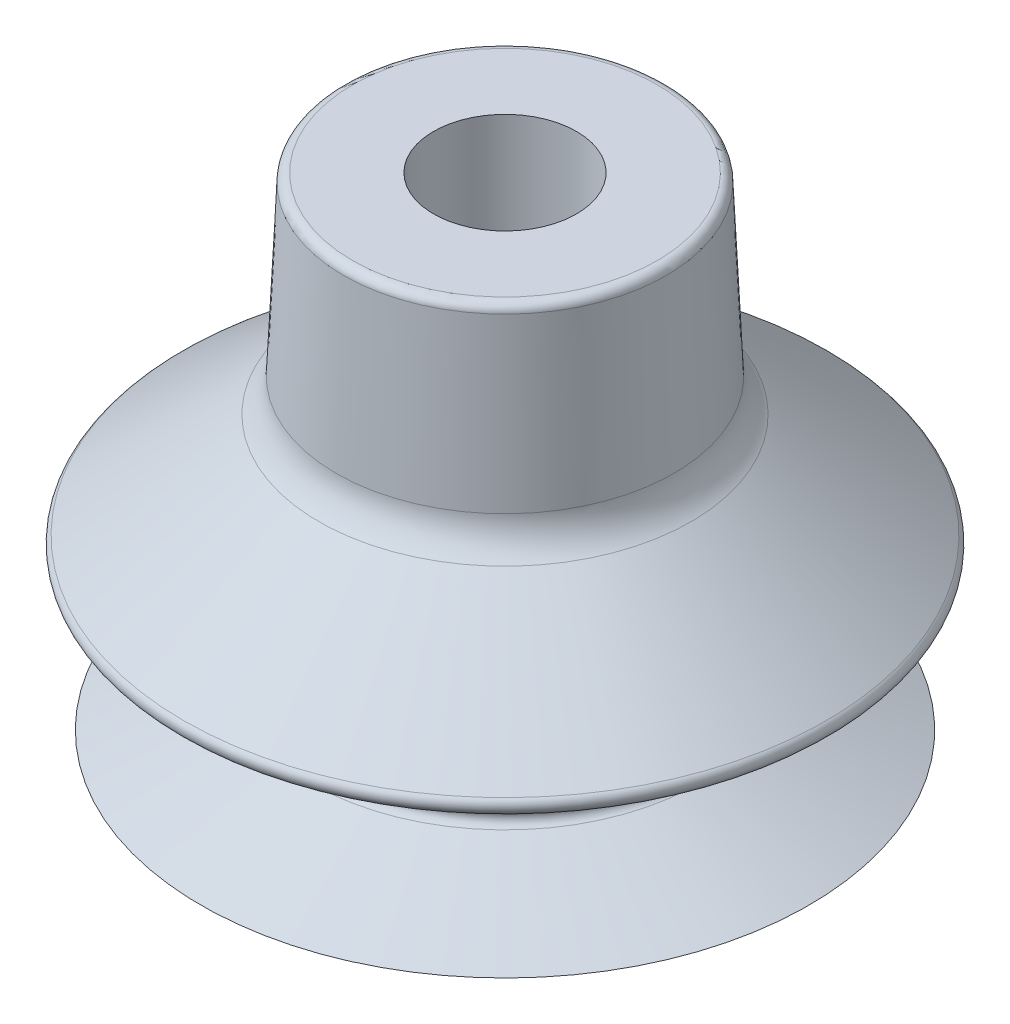
SolidWorks part; units mm, degrees
material "Nylon 6/10"
ref_plane "Plan de face" through (0, 0, 0) normal (0, 0, 1) x (1, 0, 0)
ref_plane "Plan de dessus" through (0, 0, 0) normal (0, 1, 0) x (1, 0, 0)
ref_plane "Plan de droite" through (0, 0, 0) normal (1, 0, 0) x (0, 0, -1)
sketch "Esquisse1" plane through (0, 0, 0) normal (0, 0, 1) x (1, 0, 0)
  line L0 (0, 0) -> (0, 18) construction
  line L2 (4, 18) -> (9, 18)
  line L3 (9, 18) -> (9.5, 7)
  line L4 (9.5, 7) -> (18.5, 0)
  line L5 (18.5, 0) -> (10.0239, -5.8229)
  line L6 (10.0239, -5.8229) -> (17, -9)
  line L7 (17, -9) -> (14.5873, -9)
  line L8 (14.5873, -9) -> (8, -6)
  line L9 (16.8068, 0.0501) -> (10.4426, 5)
  line L10 (10.4426, 5) -> (4, 5)
  line L11 (4, 5) -> (4, 18)
  line L12 (16.8068, 0.0501) -> (8, -6)
  dimension "D1" = 18
  dimension "D2" = 13
  dimension "D3" = 8
  dimension "D4" = 18
  dimension "D5" = 19
  dimension "D6" = 11
  dimension "D7" = 37
  dimension "D8" = 1
  dimension "D9" = 1
  dimension "D10" = 1
  dimension "D11" = 27
  dimension "D12" = 34
  dimension "D13" = 18
  dimension "D14" = 16
  dimension "D15" = 24
revolve "Révolution1" add sketch "Esquisse1" angle 360 about L0
fillet "Congé1" radius 0.5 6 edges at (0, 18, -9) (0, 0.0501, -16.8068) (0, 0, -18.5) (0, -5.8229, -10.0239) (0, -6, -8) (0, 5, -10.4426)
fillet "Congé2" radius 2.5 1 edges at (0, 7, -9.5)
